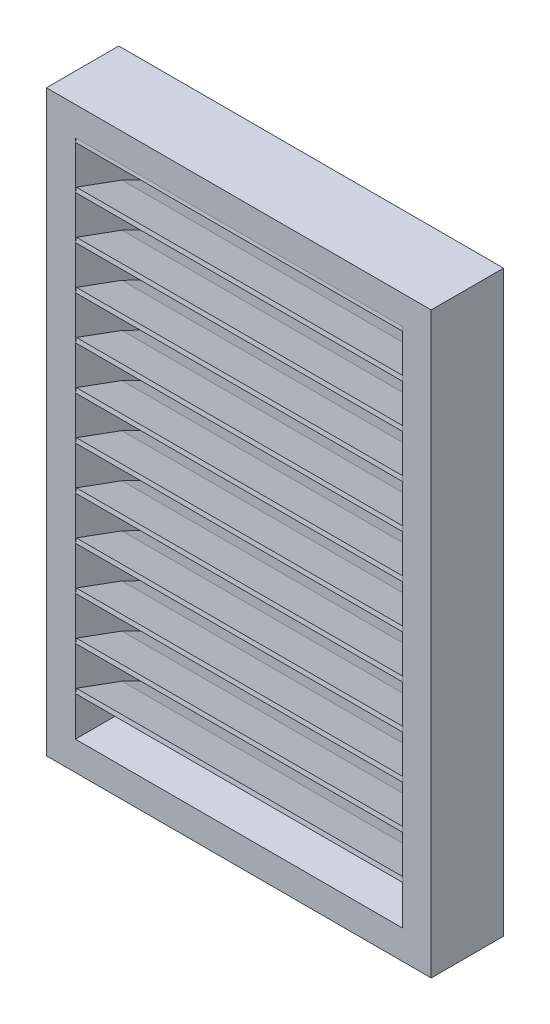
SolidWorks part; units mm, degrees
material "Plain Carbon Steel"
ref_plane "Front Plane" through (0, 0, 0) normal (0, 0, 1) x (1, 0, 0)
ref_plane "Top Plane" through (0, 0, 0) normal (0, 1, 0) x (1, 0, 0)
ref_plane "Right Plane" through (0, 0, 0) normal (1, 0, 0) x (0, 0, -1)
sketch "Sketch2" plane through (0, 0, 0) normal (0, 0, 1) x (1, 0, 0)
  line L1 (0, 0) -> (1330, 0)
  line L2 (0, 0) -> (0, 2000)
  line L3 (0, 2000) -> (1330, 2000)
  line L4 (1330, 0) -> (1330, 2000)
  line L5 (100, 1900) -> (1230, 1900)
  line L6 (100, 1900) -> (100, 100)
  line L7 (100, 100) -> (1230, 100)
  line L8 (1230, 1900) -> (1230, 100)
  dimension "D1" = 1330
  dimension "D2" = 2000
  dimension "D3" = 100
  dimension "D4" = 100
  dimension "D5" = 100
  dimension "D6" = 100
extrude "Boss-Extrude1" add sketch "Sketch2" along normal blind 250
sketch "Sketch3" plane through (1230, 0, 0) normal (-1, 0, 0) x (0, 0, 1)
  line L0 (246.7656, 250.8625) -> (89.1261, 193.0886)
  line L1 (89.1261, 193.0886) -> (1.0101, 150.2336)
  line L2 (1.0101, 150.2336) -> (7.5706, 136.7443)
  line L3 (7.5706, 136.7443) -> (96.5995, 180.0433)
  line L4 (96.5995, 180.0433) -> (249.4432, 236.0596)
  line L5 (249.4432, 236.0596) -> (246.7656, 250.8625)
  dimension "D1" = 15
extrude "Boss-Extrude7" add sketch "Sketch3" along normal up to vertex (1130 mm away)
pattern_linear "LPattern1" count 12 spacing 150 along (0, 1, 0) of "Boss-Extrude7"
